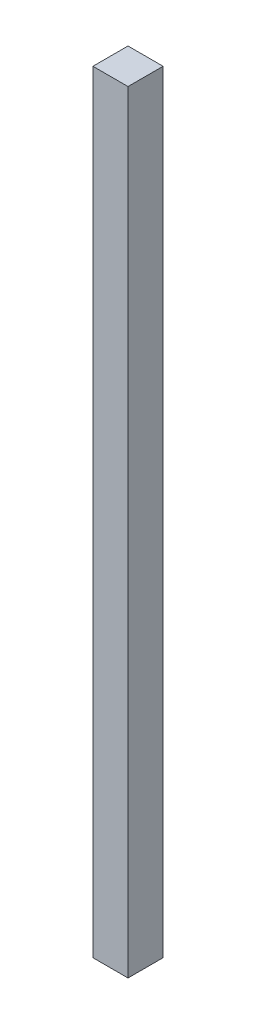
SolidWorks part; units mm, degrees
ref_plane "Front Plane" through (0, 0, 0) normal (0, 0, 1) x (1, 0, 0)
ref_plane "Top Plane" through (0, 0, 0) normal (0, 1, 0) x (1, 0, 0)
ref_plane "Right Plane" through (0, 0, 0) normal (1, 0, 0) x (0, 0, -1)
sketch "Sketch1" plane through (0, 0, 0) normal (0, 1, 0) x (1, 0, 0)
  line L1 (-10, 10) -> (10, 10)
  line L2 (-10, 10) -> (-10, -10)
  line L3 (-10, -10) -> (10, -10)
  line L4 (10, 10) -> (10, -10)
  line L5 (-10, 10) -> (10, -10) construction
  line L6 (-10, -10) -> (10, 10) construction
  point P0 (0, 0)
  dimension "D1" = 20
  dimension "D2" = 20
extrude "Boss-Extrude1" add sketch "Sketch1" along normal blind 440
